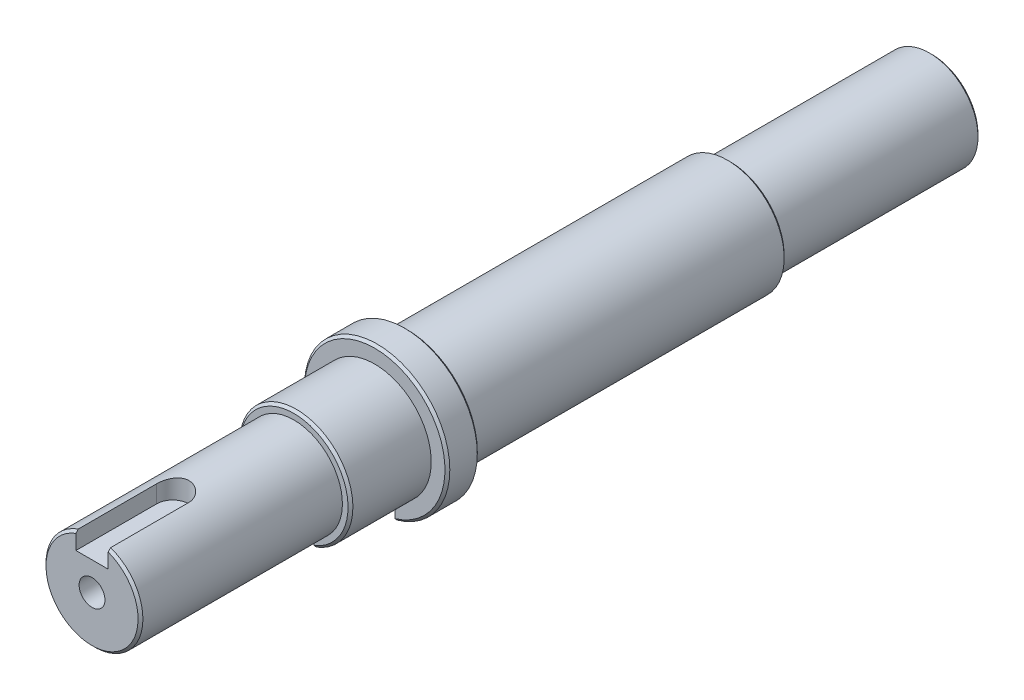
SolidWorks part; units mm, degrees
material "镀铬不锈钢"
ref_plane "前视基准面" through (0, 0, 0) normal (0, 0, 1) x (1, 0, 0)
ref_plane "上视基准面" through (0, 0, 0) normal (0, 1, 0) x (1, 0, 0)
ref_plane "右视基准面" through (0, 0, 0) normal (1, 0, 0) x (0, 0, -1)
sketch "Sketch1" plane through (0, 0, 0) normal (0, 0, 1) x (1, 0, 0)
  circle A0 centre (0, 0) radius 7
  dimension "D1" = 14
extrude "Extrude1" add sketch "Sketch1" along normal mid plane 74
sketch "Sketch5" plane through (0, 0, 37) normal (0, 0, 1) x (1, 0, 0)
  circle A2 centre (0, 0) radius 9
  circle A3 centre (0, 0) radius 9
  dimension "D1" = 2
extrude "Extrude5" add sketch "Sketch5" against normal blind 4 from offset 20 offset against normal yes
sketch "Sketch3" plane through (0, 0, 0) normal (0, 1, 0) x (1, 0, 0)
  line L0 (0, -27) -> (0, -17) construction
  line L1 (-2.5, -27) -> (-2.5, -17)
  line L2 (2.5, -27) -> (2.5, -17)
  line L3 (-7, -37) -> (7, -37) construction
  arc A0 (-2.5, -27) -> (2.5, -27) centre (0, -27) ccw
  arc A1 (2.5, -17) -> (-2.5, -17) centre (0, -17) ccw
  point P2 (0, -22)
  dimension "D1" = 5
  dimension "D2" = 10
  dimension "D3" = 10
extrude "Extrude3" cut sketch "Sketch3" against normal through all from offset 4 offset against normal yes
sketch "Sketch4" plane through (0, 0, 37) normal (0, 0, 1) x (1, 0, 0)
  circle A0 centre (0, 0) radius 6
  circle A2 centre (0, 0) radius 7
  circle A3 centre (0, 0) radius 7
  dimension "D1" = 12
  dimension "D2" = 0
extrude "Extrude4" cut sketch "Sketch4" against normal blind 10
mirror "Mirror1" about plane through (0, 0, 0) normal (0, 0, 1) of "Extrude4"
sketch "Sketch6" plane through (0, 0, 37) normal (0, 0, 1) x (1, 0, 0)
  circle A1 centre (0, 0) radius 6
  circle A2 centre (0, 0) radius 6
  dimension "D1" = 0
extrude "Extrude6" add sketch "Sketch6" along normal blind 15
mirror "Mirror2" about plane through (0, 0, 0) normal (0, 0, 1) of "Extrude6"
chamfer "Chamfer1" distance 0.3 angle 45 6 edges at (6, 0, 52) (6, 0, -52) (7, 0, -27) (9, 0, 13) (0, 9, 17) (0, 7, 27)
sketch "Sketch7" plane through (0, 0, 52) normal (0, 0, 1) x (1, 0, 0)
  circle A0 centre (0, 0) radius 1.6
  dimension "D1" = 3.2
extrude "Extrude7" cut sketch "Sketch7" against normal blind 12
cosmetic thread "Cosmetic Thread1" parameters "D1"=10, "D2"=4
mirror "Mirror3" about plane through (0, 0, 0) normal (0, 0, 1) of "Extrude7"
cosmetic thread "装饰螺纹线1" parameters "D1"=10, "D2"=4
sketch "Sketch8" plane through (0, 0, 0) normal (0, 1, 0) x (1, 0, 0)
  line L0 (0, 52) -> (0, 42) construction
  line L1 (1.6, 52) -> (-1.6, 52) construction
  line L2 (2, 52) -> (2, 42)
  line L3 (-2, 52) -> (-2, 42)
  arc A0 (2, 52) -> (-2, 52) centre (0, 52) ccw
  arc A1 (-2, 42) -> (2, 42) centre (0, 42) ccw
  point P5 (0, 47)
  dimension "D1" = 10
  dimension "D2" = 4
extrude "Extrude8" cut sketch "Sketch8" against normal blind 12 from offset 3.5 offset against normal yes
sketch "Sketch9" plane through (0, 0, 0) normal (0, 1, 0) x (1, 0, 0)
  line L0 (0, -52) -> (0, -42) construction
  line L1 (-5.7, -52) -> (5.7, -52) construction
  line L2 (-2, -52) -> (-2, -42)
  line L3 (2, -52) -> (2, -42)
  arc A0 (-2, -52) -> (2, -52) centre (0, -52) ccw
  arc A1 (2, -42) -> (-2, -42) centre (0, -42) ccw
  point P5 (0, -47)
  dimension "D1" = 10
  dimension "D2" = 4
extrude "Extrude9" cut sketch "Sketch9" along normal through all from offset 3.5
